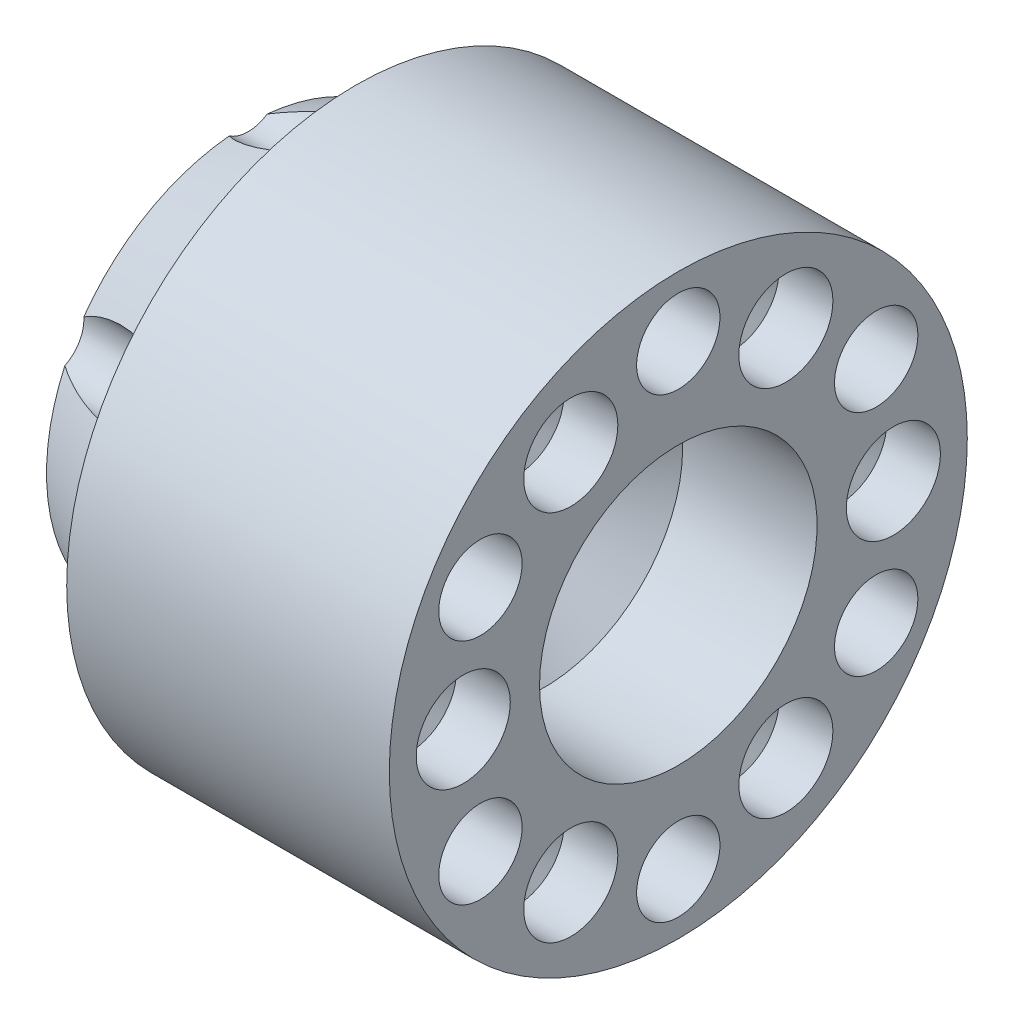
SolidWorks part; units mm, degrees
material "2018 Alloy"
ref_plane "Front Plane" through (0, 0, 0) normal (0, 0, 1) x (1, 0, 0)
ref_plane "Top Plane" through (0, 0, 0) normal (0, 1, 0) x (1, 0, 0)
ref_plane "Right Plane" through (0, 0, 0) normal (1, 0, 0) x (0, 0, -1)
sketch "Sketch1" plane through (0, 0, 0) normal (0, 0, 1) x (1, 0, 0)
  line L2 (8, 18.5) -> (0, 15)
  line L4 (0, 8.3175) -> (0, 0) construction
  line L5 (32, 0) -> (32, 10.325) construction
  line L7 (0, 0) -> (32, 0) construction
  line L13 (32, 10.325) -> (22, 10.325)
  line L14 (22, 10.325) -> (18.175, 6.5)
  line L15 (18.175, 6.5) -> (0, 8.3175)
  line L16 (8, 18.5) -> (8, 21.5)
  line L17 (8, 21.5) -> (32, 21.5)
  line L18 (0, 15) -> (0, 8.3175)
  line L26 (32, 21.5) -> (32, 10.325)
  line L27 (18.175, 6.5) -> (8.175, 6.5) construction
  line L28 (8.175, 6.5) -> (8.175, 7.5) construction
  dimension "D4" = 32
  dimension "D5" = 24
  dimension "D6" = 10
  dimension "D8" = 20.65
  dimension "D9" = 45
  dimension "D10" = 13
  dimension "D13" = 8
  dimension "D14" = 37
  dimension "D15" = 30
  dimension "D16" = 43
  dimension "D17" = 66.371
  dimension "D19" = 18.175
  dimension "D20" = 10
  dimension "D27" = 1
  dimension "D28" = 5.711
  dimension "D29" = 16.635
  dimension "D31" = 3.825
revolve "Revolve1" add sketch "Sketch1" angle 360 about L7
sketch "Sketch11" plane through (32, 0, 0) normal (1, 0, 0) x (0, 0, -1)
  line L0 (0, 0) -> (0, -17) construction
  circle A0 centre (0, 0) radius 17 construction
  circle A1 centre (0, -17) radius 3.1
  circle A2 centre (-14.7224, -8.5) radius 3.1
  circle A3 centre (-14.7224, 8.5) radius 3.1
  circle A4 centre (0, 17) radius 3.1
  circle A5 centre (14.7224, 8.5) radius 3.1
  circle A6 centre (14.7224, -8.5) radius 3.1
  dimension "D1" = 34
  dimension "D2" = 6.2
extrude "Extrude1" cut sketch "Sketch11" against normal blind 12
sketch "Sketch12" plane through (20, 0, 0) normal (1, 0, 0) x (0, 0, -1)
  circle A0 centre (0, -17) radius 3
  circle A1 centre (-14.7224, -8.5) radius 3
  circle A2 centre (-14.7224, 8.5) radius 3
  circle A3 centre (0, 17) radius 3
  circle A4 centre (14.7224, 8.5) radius 3
  circle A5 centre (14.7224, -8.5) radius 3
  dimension "D1" = 6
hole_wizard "M6 Tapped Hole1" positions "3DSketch1" profile "Sketch13" tap size "M6" standard "DIN"
sketch3d "3DSketch1"
  point P0 (20, -17, 0)
  point P3 (20, -8.5, 14.7224)
  point P6 (20, 8.5, 14.7224)
  point P9 (20, 17, 0)
  point P12 (20, 8.5, -14.7224)
  point P15 (20, -8.5, -14.7224)
sketch "Sketch13" plane through (20, -17, 0) normal (0, 1, 0) x (0, 0, -1)
  line L0 (0, 0) -> (0, 36.5022)
  line L1 (0, 36.5022) -> (2.5, 35)
  line L2 (2.5, 35) -> (2.5, 0)
  line L5 (2.5, 0) -> (0, 0)
  line L10 (0, 36.5022) -> (-2.5, 35) construction
  line L11 (0, -6.35) -> (0, 107.95) construction
  dimension "Tap Drill Dia." = 5
  dimension "Tap Drill Depth" = 35
  dimension "Drill Angle" = 118
cosmetic thread "Hole Thread3"
cosmetic thread "Hole Thread4"
cosmetic thread "Hole Thread5"
cosmetic thread "Hole Thread6"
cosmetic thread "Hole Thread7"
cosmetic thread "Hole Thread8"
sketch "Sketch14" plane through (32, 0, 0) normal (1, 0, 0) x (0, 0, -1)
  line L0 (0, -16) -> (0, 0) construction
  line L1 (0, 0) -> (8, -13.8564) construction
  circle A0 centre (0, 0) radius 16 construction
  circle A1 centre (8, -13.8564) radius 3.5
  circle A2 centre (-8, -13.8564) radius 3.5
  circle A3 centre (-16, 0) radius 3.5
  circle A4 centre (-8, 13.8564) radius 3.5
  circle A5 centre (8, 13.8564) radius 3.5
  circle A6 centre (16, 0) radius 3.5
  dimension "D1" = 32
  dimension "D3" = 7
  dimension "D2" = 30
hole_wizard "Ø7.0 (7) Diameter Hole1" positions "3DSketch2" profile "Sketch15" hole size "Ø7.0" standard "DIN"
sketch3d "3DSketch2"
  point P0 (32, -13.8564, -8)
  point P3 (32, -13.8564, 8)
  point P6 (32, 0, 16)
  point P9 (32, 13.8564, 8)
  point P12 (32, 13.8564, -8)
  point P15 (32, 0, -16)
sketch "Sketch15" plane through (32, -13.8564, -8) normal (0, 1, 0) x (0, 0, -1)
  line L0 (0, 0) -> (0, 6.103)
  line L1 (0, 6.103) -> (3.5, 4)
  line L2 (3.5, 4) -> (3.5, 0)
  line L5 (3.5, 0) -> (0, 0)
  line L10 (0, 6.103) -> (-3.5, 4) construction
  line L11 (0, -6.35) -> (0, 107.95) construction
  dimension "Hole Dia." = 7
  dimension "Hole Depth" = 4
  dimension "Drill Angle" = 118
sketch "Sketch17" plane through (0, 0, 0) normal (0, 0, 1) x (1, 0, 0)
  line L0 (0, 0) -> (0, 33.2506)
sketch "Sketch18" plane through (0, 0, 0) normal (0, 0, 1) x (1, 0, 0)
  line L0 (21.0706, 5.306) -> (-1.0846, 7.5215)
  line L1 (-1.0846, 7.5215) -> (-0.7861, 10.5066)
  line L2 (-0.7861, 10.5066) -> (21.3691, 8.2911)
  line L3 (21.3691, 8.2911) -> (21.0706, 5.306)
  line L4 (18.175, 6.5) -> (0, 8.3175) construction
  dimension "D1" = 2.1
  dimension "D2" = 3
  dimension "D3" = 1
  dimension "D4" = 3
extrude "Extrude3" cut sketch "Sketch18" against normal mid plane 2
